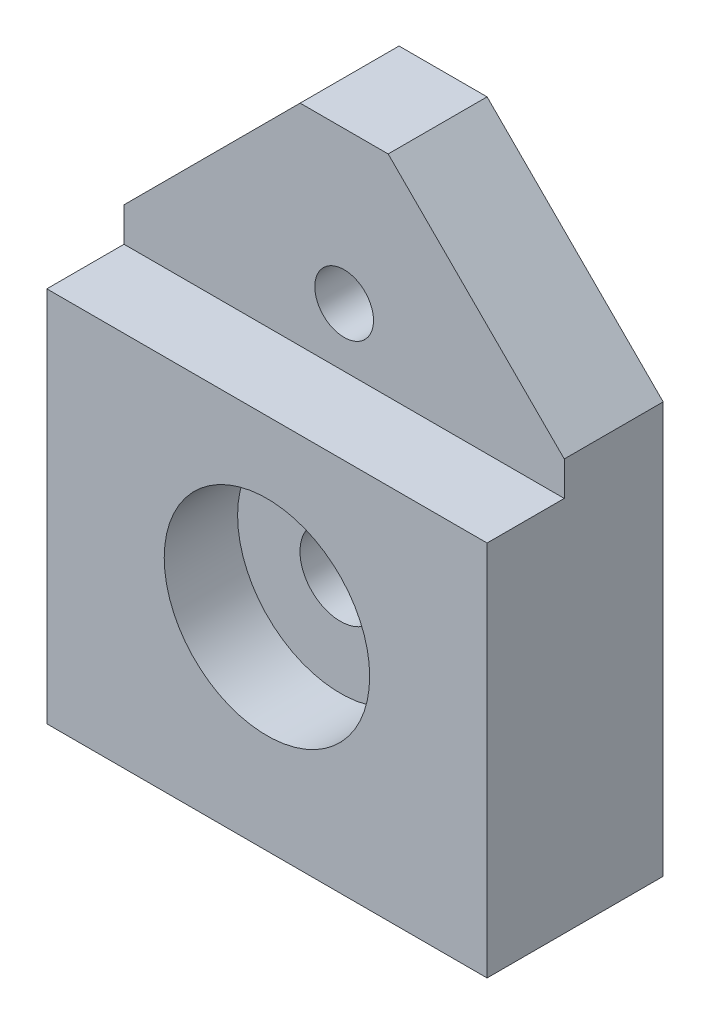
SolidWorks part; units mm, degrees
ref_plane "Plano frontal" through (0, 0, 0) normal (0, 0, 1) x (1, 0, 0)
ref_plane "Plano superior" through (0, 0, 0) normal (0, 1, 0) x (1, 0, 0)
ref_plane "Plano direito" through (0, 0, 0) normal (1, 0, 0) x (0, 0, -1)
sketch "Esboço1" plane through (0, 0, 0) normal (0, 0, 1) x (1, 0, 0)
  line L0 (69.0448, -26.9219) -> (81.0448, -38.9219)
  line L1 (51.0448, -66.9219) -> (81.0448, -66.9219)
  line L2 (51.0448, -66.9219) -> (51.0448, -38.9219)
  line L3 (63.0448, -26.9219) -> (69.0448, -26.9219)
  line L4 (81.0448, -66.9219) -> (81.0448, -38.9219)
  line L5 (51.0448, -38.9219) -> (63.0448, -26.9219)
  point P1 (81.0448, -26.9219)
  point P2 (51.0448, -26.9219)
  dimension "D1" = 40
  dimension "D2" = 30
  dimension "D5" = 12
  dimension "D6" = 12
extrude "Ressalto-extrusão1" add sketch "Esboço1" along normal blind 12
hole_wizard "Furo com folga de M51" positions "Esboço8" profile "Esboço7" hole size "M5" standard "Métrico Ansi" end condition up to next
sketch "Esboço8" plane through (0, 0, 12) normal (0, 0, 1) x (1, 0, 0)
  line L3 (51.0448, -38.9219) -> (51.0448, -66.9219) construction
  line L4 (51.0448, -66.9219) -> (81.0448, -66.9219) construction
  point P0 (66.0448, -53.1219)
  point P14 (66.5929, -63.7299)
  dimension "D1" = 15
  dimension "D2" = 13.8
sketch "Esboço7" plane through (66.0448, -53.1219, 12) normal (1, 0, 0) x (0, -1, 0)
  line L0 (0, 0) -> (0, 12)
  line L1 (0, 12) -> (2.75, 12)
  line L2 (2.75, 12) -> (2.75, 0)
  line L5 (2.75, 0) -> (0, 0)
  line L11 (0, -6.35) -> (0, 107.95) construction
  dimension "Thru Hole Dia." = 5.5
  dimension "Thru Hole Depth" = 12
sketch "Esboço9" plane through (0, 0, 12) normal (0, 0, 1) x (1, 0, 0)
  circle A0 centre (66.0448, -53.1219) radius 7
  dimension "D1" = 14
extrude "Corte-extrusão3" cut sketch "Esboço9" against normal blind 5
sketch "Esboço10" plane through (0, 0, 12) normal (0, 0, 1) x (1, 0, 0)
  line L0 (51.0448, -41.2511) -> (51.0448, -38.9219)
  line L1 (51.0448, -38.9219) -> (51.0448, -66.9219) construction
  line L2 (51.0448, -38.9219) -> (63.0448, -26.9219)
  line L3 (63.0448, -26.9219) -> (69.0448, -26.9219)
  line L4 (69.0448, -26.9219) -> (81.0448, -38.9219)
  line L5 (81.0448, -38.9219) -> (81.0448, -41.2511)
  line L6 (81.0448, -66.9219) -> (81.0448, -38.9219) construction
  line L7 (81.0448, -41.2511) -> (51.0448, -41.2511)
extrude "Corte-extrusão4" cut sketch "Esboço10" against normal blind 5.26
hole_wizard "Furo de diâmetro Ø4.0 (4)1" positions "Esboço12" profile "Esboço11" hole size "Ø4.0" standard "Métrico Ansi"
sketch "Esboço12" plane through (0, 0, 6.74) normal (0, 0, 1) x (1, 0, 0)
  line L0 (51.0448, -41.2511) -> (81.0448, -41.2511) construction
  line L1 (51.0448, -38.9219) -> (51.0448, -41.2511) construction
  point P0 (66.0448, -37.2511)
  point P8 (51.0448, -39.9665)
  point P15 (54.0933, -40.8613)
  point P16 (51.0448, -40.0865)
  point P17 (51.0448, -40.0865)
  dimension "D1" = 4
  dimension "D2" = 15
sketch "Esboço11" plane through (66.0448, -37.2511, 6.74) normal (1, 0, 0) x (0, -1, 0)
  line L0 (0, 0) -> (0, 7.9417)
  line L1 (0, 7.9417) -> (2, 6.74)
  line L2 (2, 6.74) -> (2, 0)
  line L5 (2, 0) -> (0, 0)
  line L10 (0, 7.9417) -> (-2, 6.74) construction
  line L11 (0, -6.35) -> (0, 107.95) construction
  dimension "Hole Dia." = 4
  dimension "Hole Depth" = 6.74
  dimension "Drill Angle" = 118
